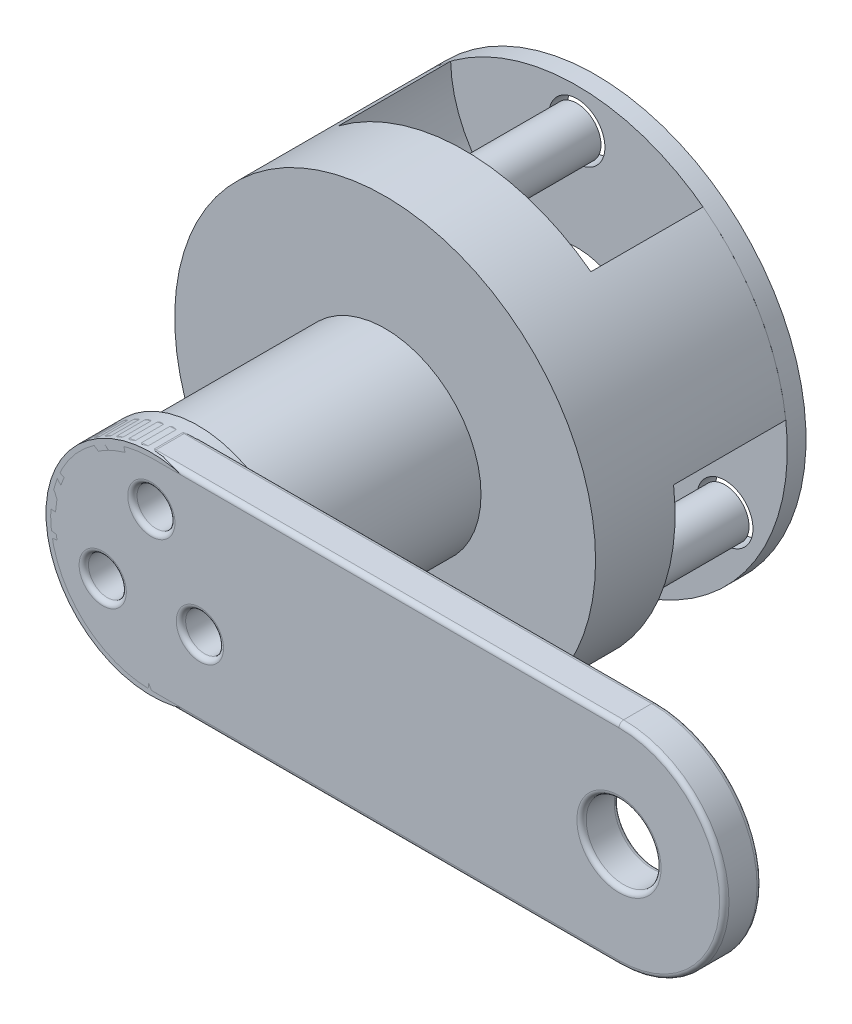
SolidWorks part; units mm, degrees
ref_plane "Front Plane" through (0, 0, 0) normal (0, 0, 1) x (1, 0, 0)
ref_plane "Top Plane" through (0, 0, 0) normal (0, 1, 0) x (1, 0, 0)
ref_plane "Right Plane" through (0, 0, 0) normal (1, 0, 0) x (0, 0, -1)
sketch "Sketch1" plane through (0, 0, 0) normal (0, 0, 1) x (1, 0, 0)
  line L0 (0, 0) -> (0, 18.28)
  line L1 (0, 0) -> (0, 18.28)
  circle A0 centre (0, 18.28) radius 13 construction
  circle A1 centre (15.8309, -9.14) radius 13 construction
  circle A2 centre (-15.8309, -9.14) radius 13 construction
  circle A3 centre (0, 0) radius 7 construction
  circle A4 centre (0, 0) radius 22.5 construction
  point P11 (0, 0)
  dimension "D1" = 26
  dimension "D5" = 14
  dimension "D2" = 45
  dimension "D4" = 18.28
  dimension "D3" = 3
sketch "Sketch2" plane through (0, 0, 0) normal (0, 0, 1) x (1, 0, 0)
  circle A0 centre (0, 0) radius 22.5
  circle A1 centre (0, 0) radius 22.5 construction
extrude "Boss-Extrude1" add sketch "Sketch2" against normal blind 17 and the other way blind 2
sketch "Sketch3" plane through (0, 0, -17) normal (0, 0, -1) x (-1, 0, 0)
  line L0 (0, 0) -> (0, 18.28) construction
  arc A0 (5.1427, 5.7979) -> (-5.1427, 5.7979) centre (0, 18.28) ccw
  arc A2 (2.4498, -7.3526) -> (7.5925, 1.5547) centre (15.8309, -9.14) ccw
  arc A3 (-7.5925, 1.5547) -> (-2.4498, -7.3526) centre (-15.8309, -9.14) ccw
  arc A6 (-5.1427, 5.7979) -> (-7.5925, 1.5547) centre (0, 0) ccw
  arc A7 (7.5925, 1.5547) -> (5.1427, 5.7979) centre (0, 0) ccw
  arc A8 (-2.4498, -7.3526) -> (2.4498, -7.3526) centre (0, 0) ccw
  dimension "D3" = 15.5
  dimension "D4" = 13.5
  dimension "D2" = 18.28
  dimension "D1" = 3
extrude "Cut-Extrude1" cut sketch "Sketch3" against normal blind 12 contours A6 A3 A8 A2 A7 A0
sketch "Sketch4" plane through (0, 0, -5) normal (0, 0, -1) x (-1, 0, 0)
  circle A0 centre (0, 18.28) radius 2.575
  dimension "D1" = 5.15
extrude "Boss-Extrude2" add sketch "Sketch4" along normal up to surface (12 mm away) and the other way blind 1.5 up to face at (13.0335, 7.5249, -17)
pattern_circular "CirPattern1" count 3 over 360 about axis through (0, 0, 0) along (0, 0, 1) of "Boss-Extrude2"
sketch "Sketch5" plane through (0, 0, -5) normal (0, 0, -1) x (-1, 0, 0)
  circle A0 centre (0, 0) radius 11.15
  dimension "D1" = 22.3
extrude "bearingHole" cut sketch "Sketch5" against normal blind 7 and the other way up to surface other way up to face at (0, -15.0497, -17)
sketch "Sketch8" plane through (0, 0, 2) normal (0, 0, 1) x (1, 0, 0)
  circle A0 centre (0, 0) radius 22.5
extrude "Boss-Extrude4" add sketch "Sketch8" along normal blind 1.5
sketch "Sketch6" plane through (0, 0, 3.5) normal (0, 0, 1) x (1, 0, 0)
  circle A0 centre (0, 0) radius 10.25
  dimension "D1" = 20.5
extrude "Boss-Extrude3" add sketch "Sketch6" along normal blind 20
fillet "Fillet1" radius 0.5 1 edges at (-11.15, 0, 2)
sketch "Sketch12" plane through (0, 0, 23.5) normal (0, 0, 1) x (1, 0, 0)
  point P0 (0, 6)
  dimension "D1" = 6
hole_wizard "Ø4.0mm Dowel Hole1" positions "Sketch12" profile "Sketch11" hole size "Ø4.0" standard "ANSI Metric"
sketch "Sketch11" plane through (0, 6, 23.5) normal (1, 0, 0) x (0, -1, 0)
  line L0 (0, 0) -> (0, 5)
  line L1 (0, 5) -> (2, 3.7983)
  line L2 (2, 3.7983) -> (2, 0.025)
  line L3 (2, 0.025) -> (2.025, 0)
  line L5 (2.025, 0) -> (0, 0)
  line L6 (-2, 0.025) -> (-2.025, 0) construction
  line L10 (0, 5) -> (-2, 3.7983) construction
  line L11 (0, -6.35) -> (0, 107.95) construction
  dimension "Hole Dia." = 4
  dimension "Hole Depth" = 5
  dimension "Near C'Sink Dia." = 4.05
  dimension "Near C'Sink Angle" = 90
  dimension "Drill Angle" = 118
pattern_circular "CirPattern2" count 3 over 360 about axis through (0, 0, 0) along (0, 0, 1) of "Ø4.0mm Dowel Hole1"
sketch "Sketch9" plane through (0, 0, -17) normal (0, 0, -1) x (-1, 0, 0)
  line L0 (0, 0) -> (0, 18.28) construction
  line L1 (0, 0) -> (9.6562, 5.575) construction
  line L2 (9.6562, 5.575) -> (20.7593, 11.9854) construction
  line L3 (0, 0) -> (15.2078, 8.7802) construction
  circle A0 centre (0, 0) radius 22.5
  circle A2 centre (0, 0) radius 7.5
  arc A3 (-22.3389, 2.6878) -> (-8.8417, -20.6899) centre (0, 0) ccw construction
  circle A4 centre (0, 18.28) radius 3
  circle A5 centre (15.8309, -9.14) radius 3
  circle A6 centre (-15.8309, -9.14) radius 3
  arc A7 (10.6432, 3.3234) -> (8.1998, 7.5555) centre (0, 0) ccw construction
  circle A8 centre (15.2078, 8.7802) radius 2.25
  circle A9 centre (0, -17.5604) radius 2.25
  circle A10 centre (-15.2078, 8.7802) radius 2.25
  dimension "D1" = 15
  dimension "D2" = 6
  dimension "D5" = 4.5
  dimension "D4" = 18.28
  dimension "D7" = 17.5604
  dimension "D3" = 3
  dimension "D6" = 3
extrude "Boss-Extrude5" add sketch "Sketch9" along normal blind 2 separate body
sketch "Sketch13" plane through (0, 0, 23.5) normal (0, 0, 1) x (1, 0, 0)
  circle A0 centre (0, 0) radius 10.265
  circle A1 centre (0, 0) radius 11.265
  dimension "D1" = 1
  dimension "D2" = 20.53
extrude "Boss-Extrude6" add sketch "Sketch13" along normal blind 5 separate body
sketch "Sketch14" plane through (0, 0, 28.5) normal (0, 0, 1) x (1, 0, 0)
  line L0 (0, 0) -> (50, 0) construction
  line L1 (0, 11.265) -> (50, 11.265)
  line L2 (0, -11.265) -> (50, -11.265)
  line L3 (0, 0) -> (0, 6) construction
  arc A0 (0, 11.265) -> (0, -11.265) centre (0, 0) ccw
  arc A1 (50, -11.265) -> (50, 11.265) centre (50, 0) ccw
  circle A2 centre (0, 0) radius 11.265 construction
  circle A3 centre (0, 6) radius 2.025
  circle A4 centre (5.1962, -3) radius 2.025
  circle A5 centre (-5.1962, -3) radius 2.025
  circle A6 centre (50, 0) radius 4
  point P3 (25, 0)
  dimension "D4" = 8
  dimension "D1" = 50
  dimension "D3" = 6
  dimension "D2" = 3
extrude "Boss-Extrude7" add sketch "Sketch14" against normal blind 4 separate body
fillet "Fillet2" radius 0.5 16 edges at (54, 0, 24.5) (25, -11.265, 24.5) (61.265, 0, 24.5) (-11.265, 0, 24.5) (25, 11.265, 24.5) (-3.1712, -3, 28.5) (7.2212, -3, 28.5) (2.025, 6, 28.5) (61.265, 0, 28.5) (25, -11.265, 28.5) (-11.265, 0, 28.5) (25, 11.265, 28.5) (54, 0, 28.5) (2.025, 6, 24.5) (7.2212, -3, 24.5) (-3.1712, -3, 24.5)
